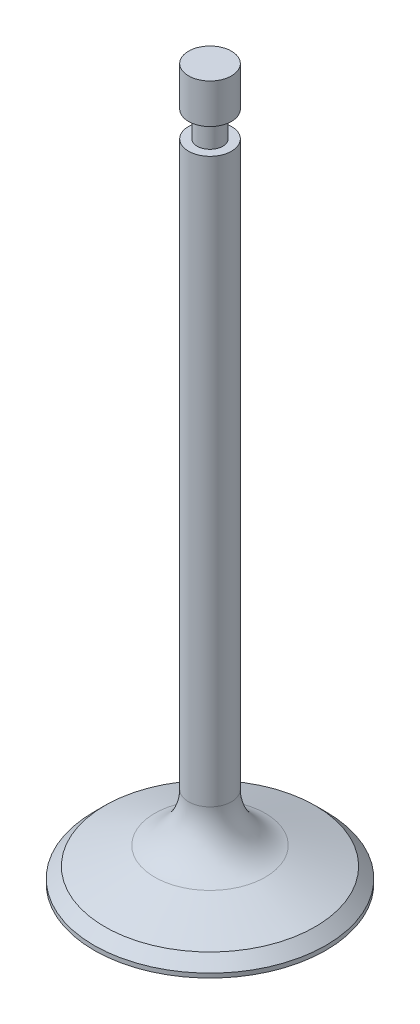
SolidWorks part; units mm, degrees
ref_plane "Plano frontal" through (0, 0, 0) normal (0, 0, 1) x (1, 0, 0)
ref_plane "Plano superior" through (0, 0, 0) normal (0, 1, 0) x (1, 0, 0)
ref_plane "Plano direito" through (0, 0, 0) normal (1, 0, 0) x (0, 0, -1)
sketch "Sketch1" plane through (0, 0, 0) normal (0, 0, 1) x (1, 0, 0)
  line L0 (0, 0) -> (0, 84)
  line L1 (0, 84) -> (2.5, 84)
  line L2 (2.5, 84) -> (2.5, 79.4)
  line L3 (2.5, 79.4) -> (1.5, 79.4)
  line L4 (1.5, 79.4) -> (1.5, 76.4)
  line L5 (1.5, 76.4) -> (2.5, 76.4)
  line L6 (2.5, 76.4) -> (2.5, 10.75)
  line L7 (6.4479, 5.1118) -> (12.25, 3)
  line L8 (12.25, 3) -> (13.5, 1.75)
  line L9 (13.5, 1.75) -> (13.5, 1.25)
  line L10 (12.25, 3) -> (0.0342, 3) construction
  line L11 (0, 0) -> (-10.9405, 0) construction
  arc A0 (2.5, 10.75) -> (6.4479, 5.1118) centre (8.5, 10.75) ccw
  arc A1 (0, 0) -> (13.5, 1.25) centre (0, 73.525) ccw
  point P12 (0, 0)
  point P20 (0, 3.6468)
  dimension "D7" = 6
  dimension "D1" = 84
  dimension "D2" = 2.5
  dimension "D3" = 1
  dimension "D4" = 3
  dimension "D5" = 4.6
  dimension "D6" = 20
  dimension "D8" = 45
  dimension "D9" = 1.25
  dimension "D10" = 0.5
  dimension "D11" = 13.5
  dimension "D12" = 1.25
revolve "Revolve1" add sketch "Sketch1" angle 360 about L0
